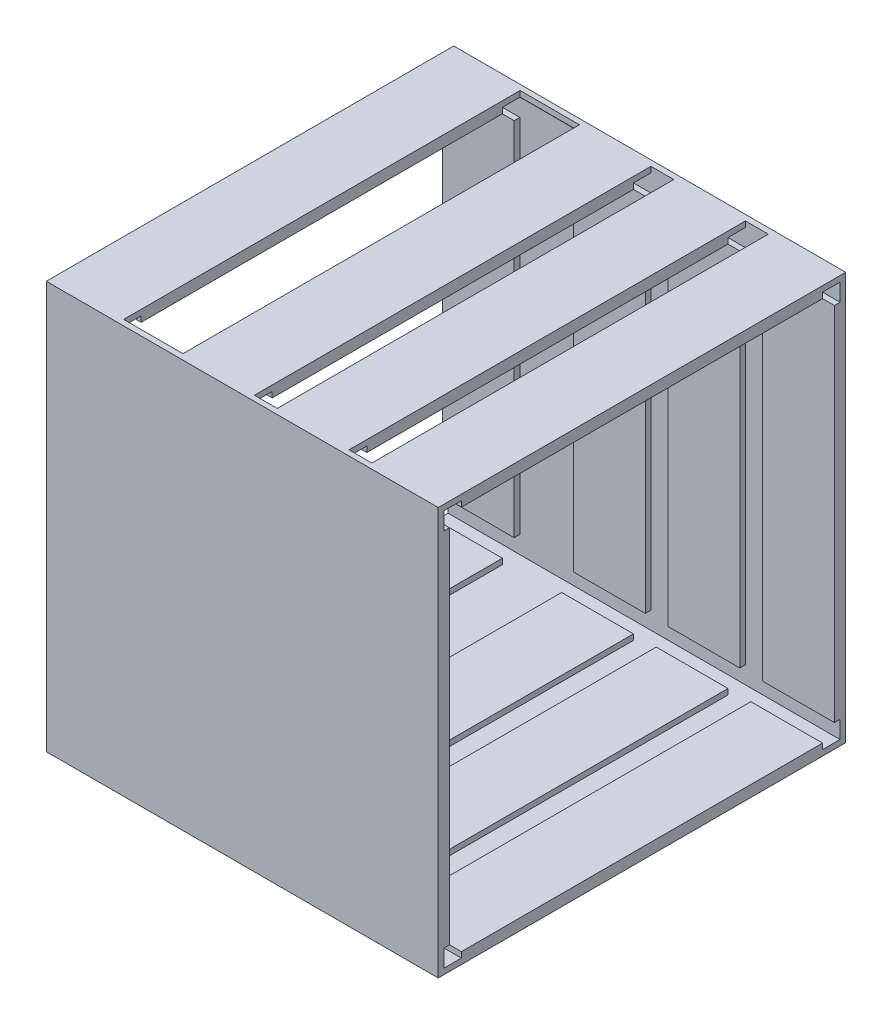
SolidWorks part; units mm, degrees
ref_plane "Front Plane" through (0, 0, 0) normal (0, 0, 1) x (1, 0, 0)
ref_plane "Top Plane" through (0, 0, 0) normal (0, 1, 0) x (1, 0, 0)
ref_plane "Right Plane" through (0, 0, 0) normal (1, 0, 0) x (0, 0, -1)
sketch "Sketch1" plane through (0, 0, 0) normal (1, 0, 0) x (0, 0, -1)
  line L1 (0, 0) -> (688.1, 0)
  line L2 (0, 0) -> (0, 688.1)
  line L3 (0, 688.1) -> (688.1, 688.1)
  line L4 (688.1, 0) -> (688.1, 688.1)
  line L5 (0, 0) -> (19.05, 0) construction
  line L6 (0, 0) -> (0, 19.05) construction
  line L7 (0, 19.05) -> (19.05, 19.05) construction
  line L8 (19.05, 0) -> (19.05, 19.05) construction
  line L9 (19.05, 19.05) -> (669.05, 19.05)
  line L10 (19.05, 19.05) -> (19.05, 669.05)
  line L11 (19.05, 669.05) -> (669.05, 669.05)
  line L12 (669.05, 19.05) -> (669.05, 669.05)
  dimension "D1" = 688.1
  dimension "D2" = 688.1
  dimension "D3" = 19.05
  dimension "D4" = 19.05
  dimension "D5" = 650
  dimension "D6" = 650
extrude "Boss-Extrude1" add sketch "Sketch1" along normal blind 661.9 contours L10 L11 L12 L9 | L2 L3 L4 L1
sketch "Sketch3" plane through (0, 0, -669.05) normal (0, 0, 1) x (1, 0, 0)
  line L1 (0, 669.05) -> (121.125, 669.05) construction
  line L2 (0, 669.05) -> (0, 19.05) construction
  line L3 (0, 19.05) -> (121.125, 19.05) construction
  line L4 (121.125, 669.05) -> (121.125, 19.05) construction
  line L5 (121.125, 669.05) -> (221.325, 669.05)
  line L6 (121.125, 669.05) -> (121.125, 19.05)
  line L7 (121.125, 19.05) -> (221.325, 19.05)
  line L8 (221.325, 669.05) -> (221.325, 19.05)
  line L9 (342.45, 669.05) -> (381.05, 669.05)
  line L10 (342.45, 669.05) -> (342.45, 19.05)
  line L11 (342.45, 19.05) -> (381.05, 19.05)
  line L12 (381.05, 669.05) -> (381.05, 19.05)
  line L13 (502.175, 669.05) -> (540.775, 669.05)
  line L14 (502.175, 669.05) -> (502.175, 19.05)
  line L15 (502.175, 19.05) -> (540.775, 19.05)
  line L16 (540.775, 669.05) -> (540.775, 19.05)
  line L17 (661.9, 688.1) -> (0, 688.1) construction
  point P15 (361.75, 669.05)
  dimension "D1" = 121.125
  dimension "D2" = 650
  dimension "D3" = 100.2
  dimension "D4" = 38.6
  dimension "D5" = 650
  dimension "D6" = 121.125
  dimension "D7" = 38.6
  dimension "D8" = 650
  dimension "D9" = 121.125
  dimension "D10" = 19.05
  dimension "D11" = 19.05
extrude "Cut-Extrude1" cut sketch "Sketch3" against normal blind 9.525
ref_plane "Plane1" through (0, 0, -344.05) normal (0, 0, -1) x (-1, 0, 0)
mirror "Mirror2" about plane through (0, 0, -344.05) normal (0, 0, -1) of "Cut-Extrude1"
ref_plane "Plane2" through (0, 344.05, 0) normal (0, 1, 0) x (1, 0, 0)
sketch "Sketch4" plane through (0, 19.05, 0) normal (0, 1, 0) x (1, 0, 0)
  line L0 (661.9, 688.1) -> (0, 688.1) construction
  line L1 (121.125, 678.575) -> (221.325, 678.575)
  line L2 (121.125, 678.575) -> (121.125, 9.075)
  line L3 (121.125, 9.075) -> (221.325, 9.075)
  line L4 (221.325, 678.575) -> (221.325, 9.075)
  line L5 (0, 0) -> (0, 688.1) construction
  line L6 (661.9, 0) -> (0, 0) construction
  line L7 (342.45, 678.575) -> (381.05, 678.575)
  line L8 (342.45, 678.575) -> (342.45, 9.075)
  line L9 (342.45, 9.075) -> (381.05, 9.075)
  line L10 (381.05, 678.575) -> (381.05, 9.075)
  line L11 (502.175, 678.575) -> (540.775, 678.575)
  line L12 (502.175, 678.575) -> (502.175, 9.525)
  line L13 (502.175, 9.525) -> (540.775, 9.525)
  line L14 (540.775, 678.575) -> (540.775, 9.525)
  dimension "D1" = 100.2
  dimension "D2" = 669.5
  dimension "D3" = 9.525
  dimension "D4" = 121.125
  dimension "D5" = 669.5
  dimension "D6" = 38.6
  dimension "D7" = 9.525
  dimension "D8" = 121.125
  dimension "D9" = 38.6
  dimension "D10" = 121.125
  dimension "D11" = 9.525
  dimension "D12" = 9.525
extrude "Cut-Extrude3" cut sketch "Sketch4" against normal blind 9.525
mirror "Mirror4" about plane through (0, 344.05, 0) normal (0, 1, 0) of "Cut-Extrude3"
sketch "Sketch6" plane through (0, 688.1, 0) normal (0, 1, 0) x (1, 0, 0)
  line L0 (0, 0) -> (0, 688.1) construction
  line L1 (121.125, 679.025) -> (221.325, 679.025)
  line L2 (121.125, 679.025) -> (121.125, 9.525)
  line L3 (121.125, 9.525) -> (221.325, 9.525)
  line L4 (221.325, 679.025) -> (221.325, 9.525)
  line L5 (342.45, 678.575) -> (381.05, 678.575)
  line L6 (342.45, 678.575) -> (342.45, 9.075)
  line L7 (342.45, 9.075) -> (381.05, 9.075)
  line L8 (381.05, 678.575) -> (381.05, 9.075)
  line L9 (502.175, 678.575) -> (540.775, 678.575)
  line L10 (502.175, 678.575) -> (502.175, 9.075)
  line L11 (502.175, 9.075) -> (540.775, 9.075)
  line L12 (540.775, 678.575) -> (540.775, 9.075)
  line L13 (661.9, 0) -> (0, 0) construction
  line L14 (661.9, 688.1) -> (0, 688.1) construction
  dimension "D1" = 669.5
  dimension "D2" = 100.2
  dimension "D3" = 121.125
  dimension "D4" = 9.525
  dimension "D5" = 38.6
  dimension "D6" = 669.5
  dimension "D7" = 9.525
  dimension "D8" = 121.125
  dimension "D9" = 38.6
  dimension "D10" = 669.5
  dimension "D11" = 9.525
  dimension "D12" = 121.125
extrude "Cut-Extrude4" cut sketch "Sketch6" against normal blind 9.525
sketch "Sketch7" plane through (0, 0, 0) normal (-1, 0, 0) x (0, 0, 1)
  line L0 (-19.05, 39.05) -> (-9.525, 39.05)
  line L1 (-19.05, 19.05) -> (-19.05, 669.05) construction
  line L2 (-9.525, 39.05) -> (-9.525, 9.525)
  line L3 (-9.525, 9.525) -> (-39.05, 9.525)
  line L4 (-39.05, 9.525) -> (-39.05, 19.05)
  line L5 (-19.05, 19.05) -> (-669.05, 19.05) construction
  line L6 (-39.05, 19.05) -> (-19.05, 19.05)
  line L7 (-19.05, 19.05) -> (-19.05, 39.05)
  dimension "D1" = 9.525
  dimension "D2" = 20
  dimension "D3" = 20
  dimension "D4" = 9.525
extrude "Cut-Extrude5" cut sketch "Sketch7" against normal blind 700
mirror "Mirror5" about plane through (0, 0, -344.05) normal (0, 0, -1) of "Cut-Extrude5"
mirror "Mirror6" about plane through (0, 344.05, 0) normal (0, 1, 0) of "Mirror5", "Cut-Extrude5"
